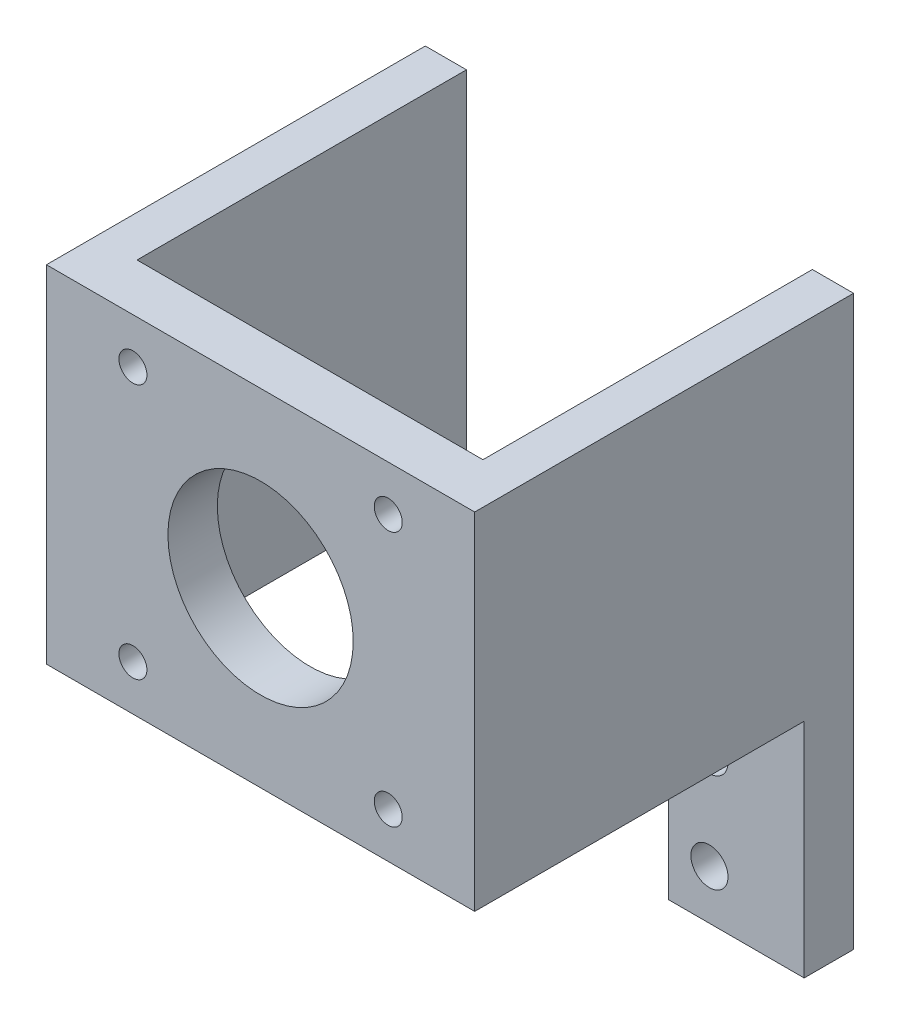
SolidWorks part; units mm, degrees
ref_plane "Спереди" through (0, 0, 0) normal (0, 0, 1) x (1, 0, 0)
ref_plane "Сверху" through (0, 0, 0) normal (0, 1, 0) x (1, 0, 0)
ref_plane "Справа" through (0, 0, 0) normal (1, 0, 0) x (0, 0, -1)
other "Configuration Table"
sketch "Фланец_эскиз" plane through (0, 0, 0) normal (0, 0, 1) x (1, 0, 0)
  line L1 (-26, -21) -> (26, -21)
  line L2 (-26, -21) -> (-26, 21)
  line L3 (-26, 21) -> (26, 21)
  line L4 (26, -21) -> (26, 21)
  line L5 (-26, -21) -> (26, 21) construction
  line L6 (-26, 21) -> (26, -21) construction
  point P0 (0, 0)
  dimension "D1" = 42
  dimension "D2" = 52
extrude "Передняя_пластина" add sketch "Фланец_эскиз" along normal blind 6 from offset 40
sketch "Скоба_эскиз" plane through (0, 0, 0) normal (0, 0, 1) x (1, 0, 0)
  line L0 (-26, -21) -> (-21, -21)
  line L1 (-21, -21) -> (-21, 21)
  line L2 (-21, 21) -> (-26, 21)
  line L3 (-26, 21) -> (-26, -21)
  line L4 (21, -21) -> (26, -21)
  line L5 (26, -21) -> (26, 21)
  line L6 (26, 21) -> (21, 21)
  line L7 (21, 21) -> (21, -21)
  line L8 (-26, -21) -> (26, -21) construction
  dimension "D1" = 5
extrude "Боковины" add sketch "Скоба_эскиз" along normal blind 40
sketch "Лапки_эскиз" plane through (0, 0, 0) normal (0, 0, 1) x (1, 0, 0)
  line L2 (-26, -21) -> (-9.5, -21)
  line L3 (-26, -21) -> (-26, -48)
  line L4 (-26, -48) -> (-9.5, -48)
  line L5 (-9.5, -48) -> (-9.5, -21)
  line L6 (9.5, -21) -> (26, -21)
  line L11 (26, -21) -> (26, -48)
  line L12 (26, -48) -> (9.5, -48)
  line L13 (9.5, -48) -> (9.5, -21)
  point P0 (26, -21)
  dimension "D1" = 16.5
  dimension "D4" = 27
extrude "Лапки_основания" add sketch "Лапки_эскиз" along normal blind 6
sketch "Крепёж_фланца_эскиз" plane through (0, 0, 0) normal (0, 0, 1) x (1, 0, 0)
  circle A0 centre (0, 0) radius 11.25
  circle A1 centre (-15.5, -15.5) radius 1.7
  circle A2 centre (-15.5, 15.5) radius 1.7
  circle A3 centre (15.5, -15.5) radius 1.7
  circle A4 centre (15.5, 15.5) radius 1.7
  dimension "D1" = 22.5
  dimension "D4" = 3.4
  dimension "D7" = 3.4
  dimension "D10" = 3.4
  dimension "D13" = 3.4
  dimension "D2" = 15.5
  dimension "D3" = 15.5
  dimension "D5" = 15.5
  dimension "D6" = 15.5
  dimension "D8" = 15.5
  dimension "D9" = 15.5
  dimension "D11" = 15.5
  dimension "D12" = 15.5
extrude "Отверстия_фланца" cut sketch "Крепёж_фланца_эскиз" against normal through all and the other way through all
sketch "Крепёж_основания_эскиз" plane through (0, 0, 0) normal (0, 0, 1) x (1, 0, 0)
  circle A0 centre (-14.5, -30) radius 2.25
  circle A1 centre (-14.5, -42) radius 2.25
  circle A2 centre (14.5, -30) radius 2.25
  circle A3 centre (14.5, -42) radius 2.25
  dimension "D3" = 4.5
  dimension "D6" = 4.5
  dimension "D9" = 4.5
  dimension "D12" = 4.5
  dimension "D1" = 14.5
  dimension "D2" = 30
  dimension "D4" = 14.5
  dimension "D5" = 42
  dimension "D7" = 14.5
  dimension "D8" = 30
  dimension "D10" = 14.5
  dimension "D11" = 42
extrude "Отверстия_основания" cut sketch "Крепёж_основания_эскиз" against normal through all and the other way through all
equation "\"Z корпус\"= 42"
equation "\"Z длина мотора\"= 40"
equation "\"Z зазор\"= 0.5"
equation "\"Z стенка\"= 5"
equation "\"Z пластина\"= 6"
equation "\"Z отступ от края\"= 2"
equation "\"Z лапка\"= 6"
equation "\"Z ширина лапки\"= 10"
equation "\"Z центр лапки\"= 14.5"
equation "\"Z задняя граница\"= 48"
equation "\"Z перекрытие\"= 3"
equation "\"Z шаг М3\"= 31"
equation "\"Z отверстие М3\"= 3.4"
equation "\"Z буртик\"= 22.5"
equation "\"Z отверстие М4\"= 4.5"
equation "\"Z первый ряд М4\"= 30"
equation "\"Z шаг М4\"= 12"
equation "\"D1@Передняя_пластина\" = \"Z пластина\""
equation "\"D19@Передняя_пластина\" = \"Z длина мотора\""
equation "\"D1@Боковины\" = \"Z длина мотора\""
equation "\"D1@Лапки_основания\" = \"Z лапка\""
equation "\"D1@Крепёж_фланца_эскиз\" = \"Z буртик\""
equation "\"D2@Крепёж_фланца_эскиз\" = \"Z шаг М3\"/2"
equation "\"D3@Крепёж_фланца_эскиз\" = \"Z шаг М3\"/2"
equation "\"D4@Крепёж_фланца_эскиз\" = \"Z отверстие М3\""
equation "\"D5@Крепёж_фланца_эскиз\" = \"Z шаг М3\"/2"
equation "\"D6@Крепёж_фланца_эскиз\" = \"Z шаг М3\"/2"
equation "\"D7@Крепёж_фланца_эскиз\" = \"Z отверстие М3\""
equation "\"D8@Крепёж_фланца_эскиз\" = \"Z шаг М3\"/2"
equation "\"D9@Крепёж_фланца_эскиз\" = \"Z шаг М3\"/2"
equation "\"D10@Крепёж_фланца_эскиз\" = \"Z отверстие М3\""
equation "\"D11@Крепёж_фланца_эскиз\" = \"Z шаг М3\"/2"
equation "\"D12@Крепёж_фланца_эскиз\" = \"Z шаг М3\"/2"
equation "\"D13@Крепёж_фланца_эскиз\" = \"Z отверстие М3\""
equation "\"D1@Крепёж_основания_эскиз\" = \"Z центр лапки\""
equation "\"D2@Крепёж_основания_эскиз\" = \"Z первый ряд М4\""
equation "\"D3@Крепёж_основания_эскиз\" = \"Z отверстие М4\""
equation "\"D4@Крепёж_основания_эскиз\" = \"Z центр лапки\""
equation "\"D5@Крепёж_основания_эскиз\" = \"Z первый ряд М4\"+\"Z шаг М4\""
equation "\"D6@Крепёж_основания_эскиз\" = \"Z отверстие М4\""
equation "\"D7@Крепёж_основания_эскиз\" = \"Z центр лапки\""
equation "\"D8@Крепёж_основания_эскиз\" = \"Z первый ряд М4\""
equation "\"D9@Крепёж_основания_эскиз\" = \"Z отверстие М4\""
equation "\"D10@Крепёж_основания_эскиз\" = \"Z центр лапки\""
equation "\"D11@Крепёж_основания_эскиз\" = \"Z первый ряд М4\"+\"Z шаг М4\""
equation "\"D12@Крепёж_основания_эскиз\" = \"Z отверстие М4\""
